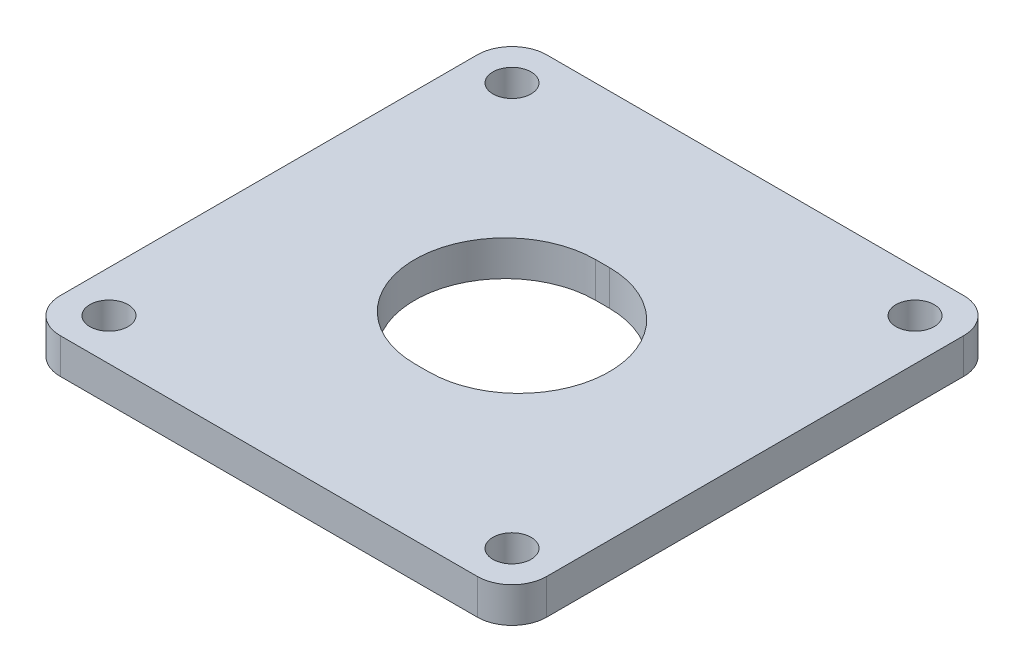
SolidWorks part; units mm, degrees
ref_plane "Front Plane" through (0, 0, 0) normal (0, 0, 1) x (1, 0, 0)
ref_plane "Top Plane" through (0, 0, 0) normal (0, 1, 0) x (1, 0, 0)
ref_plane "Right Plane" through (0, 0, 0) normal (1, 0, 0) x (0, 0, -1)
sketch "Sketch1" plane through (0, 0, 0) normal (0, 1, 0) x (1, 0, 0)
  line L0 (0, 35) -> (70, 35) construction
  line L1 (0, 0) -> (70, 0)
  line L2 (0, 0) -> (0, 70)
  line L3 (0, 70) -> (70, 70)
  line L4 (70, 0) -> (70, 70)
  line L5 (6, 64) -> (64, 64) construction
  line L6 (6, 64) -> (6, 6) construction
  line L7 (6, 6) -> (64, 6) construction
  line L8 (64, 64) -> (64, 6) construction
  line L9 (34, 35) -> (36, 35) construction
  line L10 (34, 48) -> (36, 48)
  line L11 (34, 22) -> (36, 22)
  circle A0 centre (6, 64) radius 2.75
  circle A1 centre (64, 64) radius 2.75
  circle A2 centre (64, 6) radius 2.75
  circle A3 centre (6, 6) radius 2.75
  arc A5 (34, 48) -> (34, 22) centre (34, 35) ccw
  arc A6 (36, 22) -> (36, 48) centre (36, 35) ccw
  point P17 (35, 35)
  point P22 (21, 35)
  point P23 (49, 35)
  point P24 (0, 0)
  point P25 (35, 35)
  dimension "D6" = 5.5
  dimension "D7" = 26
  dimension "D8" = 28
  dimension "D1" = 70
  dimension "D2" = 6
  dimension "D3" = 6
  dimension "D4" = 6
  dimension "D5" = 6
extrude "Boss-Extrude1" add sketch "Sketch1" along normal blind 5.08
fillet "Fillet1" radius 5 4 edges at (70, 2.54, -70) (0, 2.54, -70) (70, 2.54, 0) (0, 2.54, 0)
